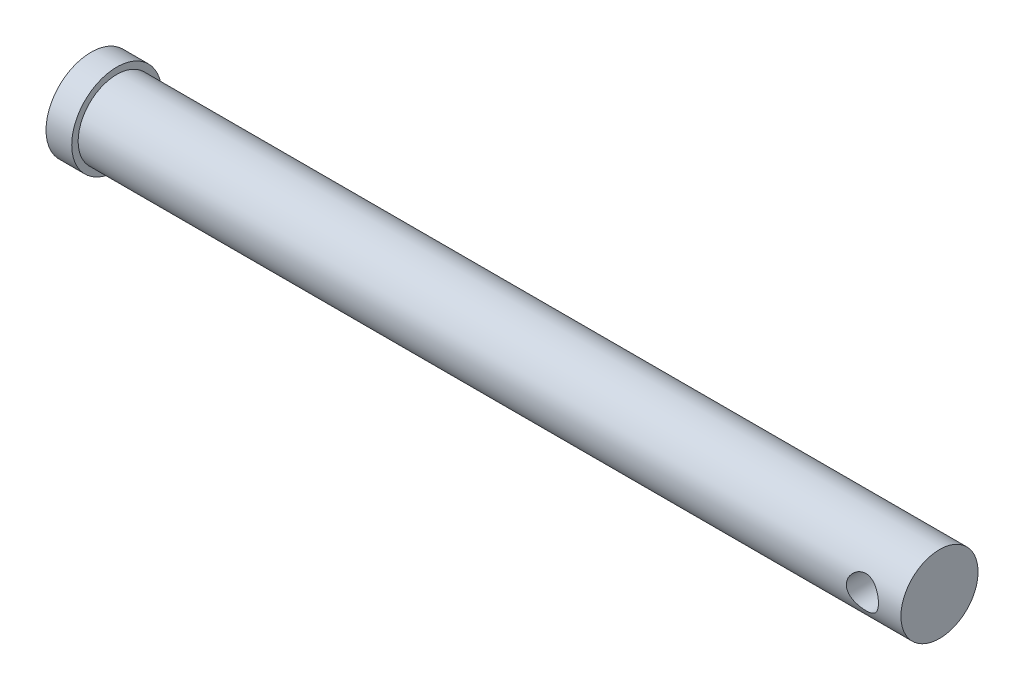
SolidWorks part; units mm, degrees
material "AISI 1020"
ref_plane "Ön Düzlem" through (0, 0, 0) normal (0, 0, 1) x (1, 0, 0)
ref_plane "Üst Düzlem" through (0, 0, 0) normal (0, 1, 0) x (1, 0, 0)
ref_plane "Sağ Düzlem" through (0, 0, 0) normal (1, 0, 0) x (0, 0, -1)
sketch "Çizim1" plane through (0, 0, 0) normal (0, 0, 1) x (1, 0, 0)
  line L0 (0, 0) -> (660, 0) construction
  line L1 (0, 0) -> (0, 35)
  line L2 (0, 35) -> (20, 35)
  line L3 (20, 35) -> (20, 30)
  line L4 (20, 30) -> (660, 30)
  line L5 (660, 30) -> (660, 0)
  line L6 (0, 0) -> (660, 0)
  dimension "D1" = 660
  dimension "D2" = 20
  dimension "D3" = 5
  dimension "D4" = 30
revolve "Döndür1" add sketch "Çizim1" angle 360 about L0
sketch "Çizim2" plane through (0, 0, 0) normal (0, 0, 1) x (1, 0, 0)
  line L0 (660, -30) -> (660, 30) construction
  circle A0 centre (630, 0) radius 12.5
  dimension "D1" = 30
  dimension "D2" = 25
extrude "Kes-Ekstrüzyon1" cut sketch "Çizim2" against normal mid plane 60
